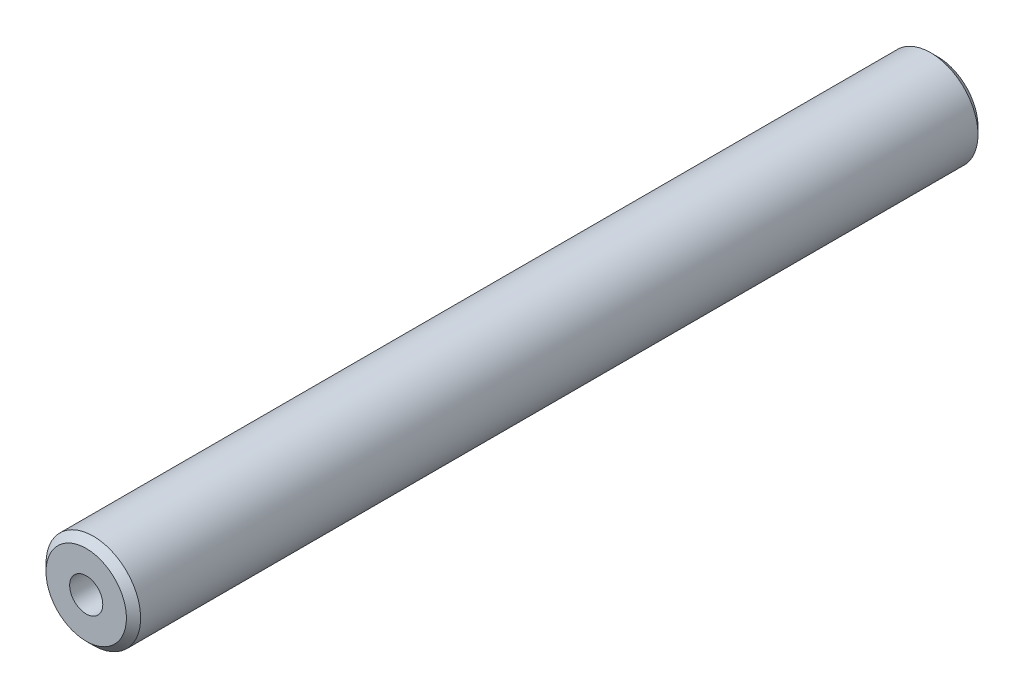
SolidWorks part; units mm, degrees
ref_plane "前视基准面" through (0, 0, 0) normal (0, 0, 1) x (1, 0, 0)
ref_plane "上视基准面" through (0, 0, 0) normal (0, 1, 0) x (1, 0, 0)
ref_plane "右视基准面" through (0, 0, 0) normal (1, 0, 0) x (0, 0, -1)
sketch "草图1" plane through (0, 0, 0) normal (0, 0, 1) x (1, 0, 0)
  circle A0 centre (0, 0) radius 10
  dimension "D1" = 20
extrude "凸台-拉伸1" add sketch "草图1" along normal blind 180
chamfer "倒角1" distance 1.5 angle 45 2 edges at (10, 0, 0) (10, 0, 180)
hole_wizard "M8x1.0 螺纹孔1" positions "3D草图1" profile "草图2" tap size "M8x1.0" standard "Gb" end condition through all
sketch3d "3D草图1"
  line L0 (0, 0, 178.5) -> (0, 0, 180) construction
  point P0 (0, 0, 180)
sketch "草图2" plane through (0, 0, 180) normal (1, 0, 0) x (0, -1, 0)
  line L0 (0, 0) -> (0, 180)
  line L1 (0, 180) -> (3.5, 180)
  line L2 (3.5, 180) -> (3.5, 0)
  line L5 (3.5, 0) -> (0, 0)
  line L11 (0, -6.35) -> (0, 107.95) construction
  dimension "通孔螺纹孔钻头直径" = 7
  dimension "通孔螺纹孔钻头深度" = 180
cosmetic thread "孔螺蚊线1" parameters "D2"=8
